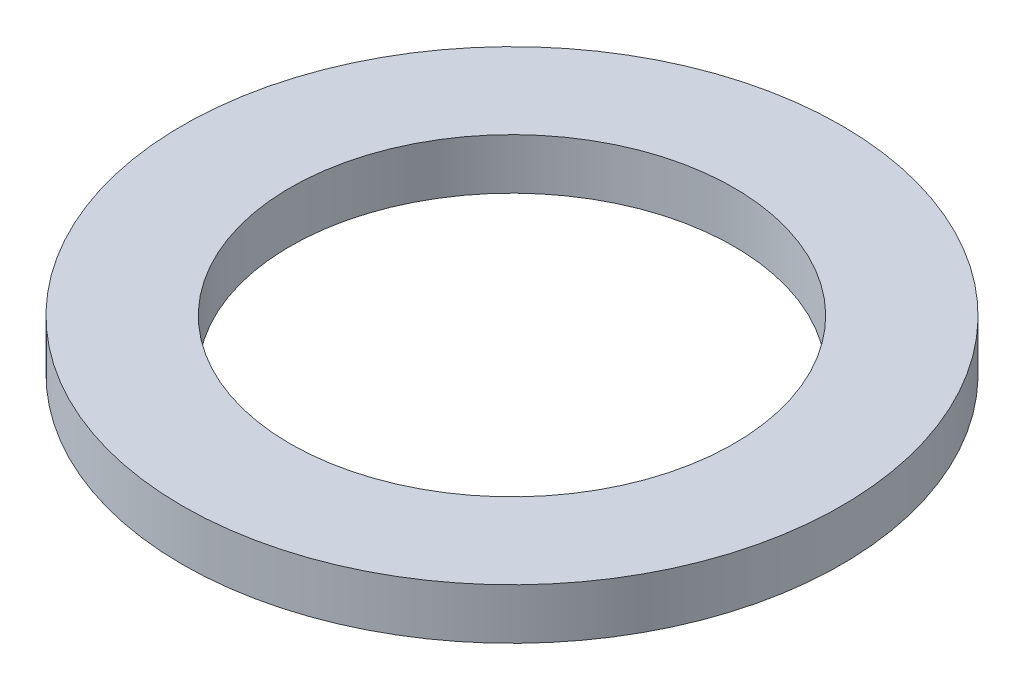
SolidWorks part; units mm, degrees
ref_plane "Ebene vorne" through (0, 0, 0) normal (0, 0, 1) x (1, 0, 0)
ref_plane "Ebene oben" through (0, 0, 0) normal (0, 1, 0) x (1, 0, 0)
ref_plane "Ebene rechts" through (0, 0, 0) normal (1, 0, 0) x (0, 0, -1)
sketch "Sketch2" plane through (0, 0, 0) normal (0, 1, 0) x (1, 0, 0)
  circle A0 centre (0, 0) radius 17.5
  circle A1 centre (0, 0) radius 26
  dimension "D1" = 35
  dimension "D2" = 52
extrude "Boss-Extrude1" add sketch "Sketch2" along normal blind 4
